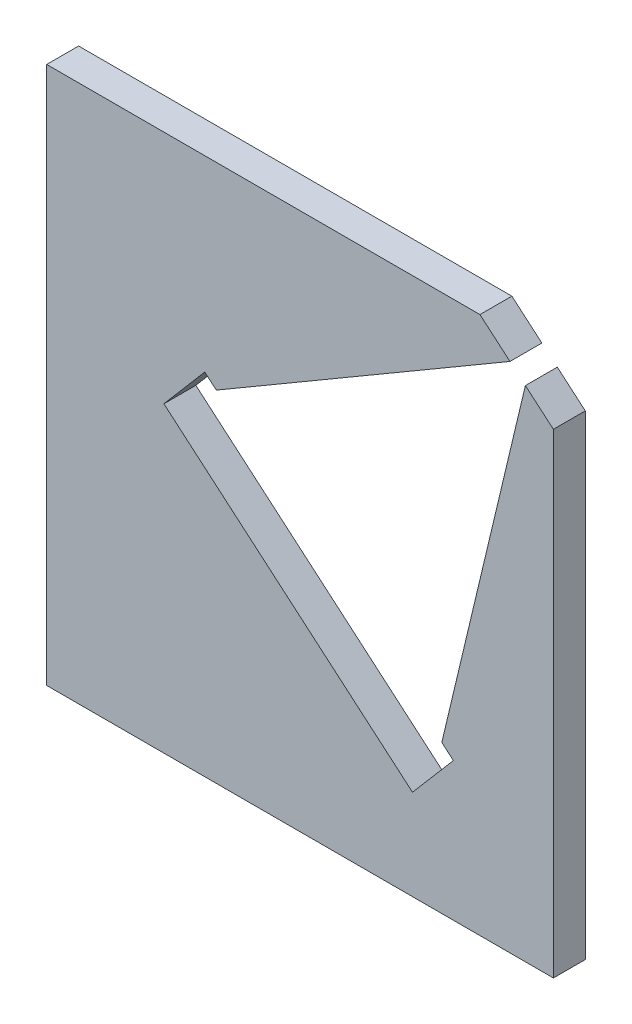
SolidWorks part; units mm, degrees
ref_plane "Front Plane" through (0, 0, 0) normal (0, 0, 1) x (1, 0, 0)
ref_plane "Top Plane" through (0, 0, 0) normal (0, 1, 0) x (1, 0, 0)
ref_plane "Right Plane" through (0, 0, 0) normal (1, 0, 0) x (0, 0, -1)
sketch "Sketch1" plane through (0, 0, 0) normal (0, 0, 1) x (1, 0, 0)
  line L6 (3.048, 23.749) -> (3.048, 14.224) construction
  line L7 (0, 0) -> (6.096, 0)
  line L8 (0, 0) -> (0, 14.224)
  line L9 (0, 14.224) -> (6.096, 14.224)
  line L14 (6.096, 0) -> (6.096, 14.224)
  line L19 (-5.124, 24.384) -> (-1.7897, 21.5391)
  line L29 (-7.3216, 0.4193) -> (-20.254, 11.4535)
  line L31 (-21.844, -3.81) -> (9.906, -3.81)
  line L33 (1.5446, 18.6941) -> (0.4377, 19.6385)
  line L34 (-20.254, 11.4535) -> (-21.844, 9.5899)
  line L35 (-1.7897, 21.5391) -> (1.5446, 18.6941)
  line L36 (-28.3165, 23.749) -> (25.4257, 23.749)
  line L37 (-28.3165, 23.749) -> (-28.3165, 38.989)
  line L38 (-28.3165, 38.989) -> (25.4257, 38.989)
  line L39 (25.4257, 23.749) -> (25.4257, 38.989)
  line L40 (3.048, 38.989) -> (3.048, 23.749) construction
  line L41 (3.048, 31.369) -> (-9.1256, 6.633) construction
  line L42 (-20.254, 11.4535) -> (-17.9459, 14.1587)
  line L43 (-7.3216, 0.4193) -> (-5.0135, 3.1244)
  line L44 (-5.0135, 3.1244) -> (-6.535, 4.4226)
  line L45 (0.4377, 19.6385) -> (0, 19.6385)
  line L46 (-17.9459, 14.1587) -> (-9.2213, 24.384)
  line L47 (-9.2213, 24.384) -> (-5.124, 24.384)
  line L48 (0, 19.6385) -> (0, 14.224)
  line L49 (-2.1762, 21.8688) -> (-17.5337, 14.6417)
  line L50 (-2.1762, 21.8688) -> (-1.4033, 21.2093)
  line L51 (-1.4033, 21.2093) -> (-5.0135, 3.1244)
  line L52 (-5.5932, 3.619) -> (3.048, 44.3318) construction
  line L53 (3.048, 38.989) -> (3.048, 44.3318) construction
  line L54 (9.906, -3.81) -> (9.906, 24.384)
  line L55 (9.906, 24.384) -> (6.096, 24.384)
  line L56 (6.096, 14.224) -> (6.096, 24.384)
  line L57 (3.048, 23.749) -> (-1.7897, 21.5391) construction
  line L58 (3.048, 38.989) -> (-1.7897, 21.5391) construction
  line L59 (-1.7897, 21.5391) -> (-6.535, 4.4226) construction
  line L60 (-1.7897, 21.5391) -> (-17.9459, 14.1587) construction
  line L61 (-17.9459, 14.1587) -> (-6.535, 4.4226)
  line L62 (-5.5932, 3.619) -> (-6.4175, 2.6529) construction
  line L63 (-6.4175, 2.6529) -> (-17.7211, 12.2975) construction
  line L64 (-17.7211, 12.2975) -> (-16.8968, 13.2636) construction
  line L69 (-16.8968, 13.2636) -> (3.048, 24.1891) construction
  line L70 (-21.844, 9.5899) -> (-21.844, -3.81)
  line L71 (-16.1239, 12.6041) -> (3.048, 24.5545) construction
  line L72 (-6.3661, 4.2785) -> (3.048, 39.7853) construction
  line L73 (-6.3661, 4.2785) -> (-7.1904, 3.3123) construction
  line L74 (-16.1239, 12.6041) -> (-16.9482, 11.638) construction
  line L75 (9.906, 24.384) -> (9.906, 25.984) construction
  line L76 (9.906, 25.984) -> (-9.2213, 25.984) construction
  line L77 (-9.2213, 25.984) -> (-9.2213, 24.384) construction
  line L78 (-17.4765, 13.7582) -> (-19.7846, 11.053)
  line L79 (-16.8968, 13.2636) -> (-2.1762, 21.8688)
  line L80 (-5.5932, 3.619) -> (-1.4033, 21.2093)
  line L81 (-21.844, 9.5899) -> (-21.844, 23.749)
  line L82 (-21.844, 23.749) -> (-21.844, 24.384)
  line L83 (-21.844, 24.384) -> (-9.2213, 24.384)
  line L84 (0, 0) -> (0, -3.81)
  line L85 (-21.844, -3.81) -> (-25.4, -3.81)
  line L86 (-25.4, -3.81) -> (-25.4, 24.384)
  line L87 (-25.4, 24.384) -> (-21.844, 24.384)
  line L88 (-15.7375, 12.2744) -> (3.048, 24.7525) construction
  line L89 (9.906, 23.1523) -> (-25.4, 23.1523)
  line L90 (-21.844, -2.2477) -> (9.906, -2.2477)
  line L91 (0, 19.6385) -> (0, 20.012)
  dimension "D1" = 6.096
  dimension "D2" = 14.224
  dimension "D3" = 0.635
  dimension "D4" = 10.16
  dimension "D5" = 3.556
  dimension "D6" = 15.24
  dimension "D7" = 17
  dimension "D8" = 31.75
  dimension "D9" = 1.59
  dimension "D10" = 1.016
  dimension "D11" = 1.016
  dimension "D12" = 3.81
  dimension "D13" = 3.81
  dimension "D14" = 0.635
  dimension "D15" = 0.508
  dimension "D16" = 0.508
  dimension "D17" = 0.762
  dimension "D18" = 14.859
  dimension "D19" = 1.27
  dimension "D20" = 15
  dimension "D21" = 1.6
  dimension "D22" = 0.762
  dimension "D23" = 3.556
  dimension "D24" = 0.508
  dimension "D25" = 1.6002
  dimension "D26" = 25.4
extrude "Boss-Extrude1" add sketch "Sketch1" along normal blind 1.6 contours L34 L70 L31 L54 L36 L56 L14 L7 L8 L48 L45 L33 L35 L19 L46 L61 L44 L43 L29 | L80 L44 L51 | L81 L34 L42 L46 L36 | L49 L19 L36 L46 | L61 L79 L49 L46 | L81 L89 L86 L85 L70 | L90 L70 L31 L84 | L78 L61 L42 L29
sketch "Sketch2" plane through (0, 0, 1.6) normal (0, 0, 1) x (1, 0, 0)
  line L0 (-19.525, 11.3573) -> (-7.062, 0.7236)
  line L2 (-7.3216, 0.4193) -> (-5.0135, 3.1244) construction
  line L3 (-7.062, 0.7236) -> (-7.3216, 0.4193)
  line L4 (-7.3216, 0.4193) -> (-19.7846, 11.053)
  line L5 (-19.7846, 11.053) -> (-19.525, 11.3573)
  point P2 (-19.7846, 11.053)
  dimension "D1" = 0.4
extrude "Boss-Extrude2" add sketch "Sketch2" against normal blind 1.6
sketch "Sketch3" plane through (0, 0, 1.6) normal (0, 0, 1) x (1, 0, 0)
  line L0 (-7.062, 0.7236) -> (-19.525, 11.3573) construction
  line L1 (-7.062, 0.7236) -> (-19.525, 11.3573)
  line L2 (-13.2935, 6.0404) -> (-12.2692, 7.2409)
  line L3 (-7.062, 0.7236) -> (-5.0135, 3.1244) construction
  line L4 (-17.4765, 13.7582) -> (-19.525, 11.3573) construction
  line L5 (-7.062, 0.7236) -> (-5.0135, 3.1244)
  line L6 (-17.4765, 13.7582) -> (-19.525, 11.3573)
  line L7 (-18.5007, 12.5577) -> (-6.0377, 1.924) construction
  point P4 (-12.2692, 7.2409)
  point P5 (0, 0)
